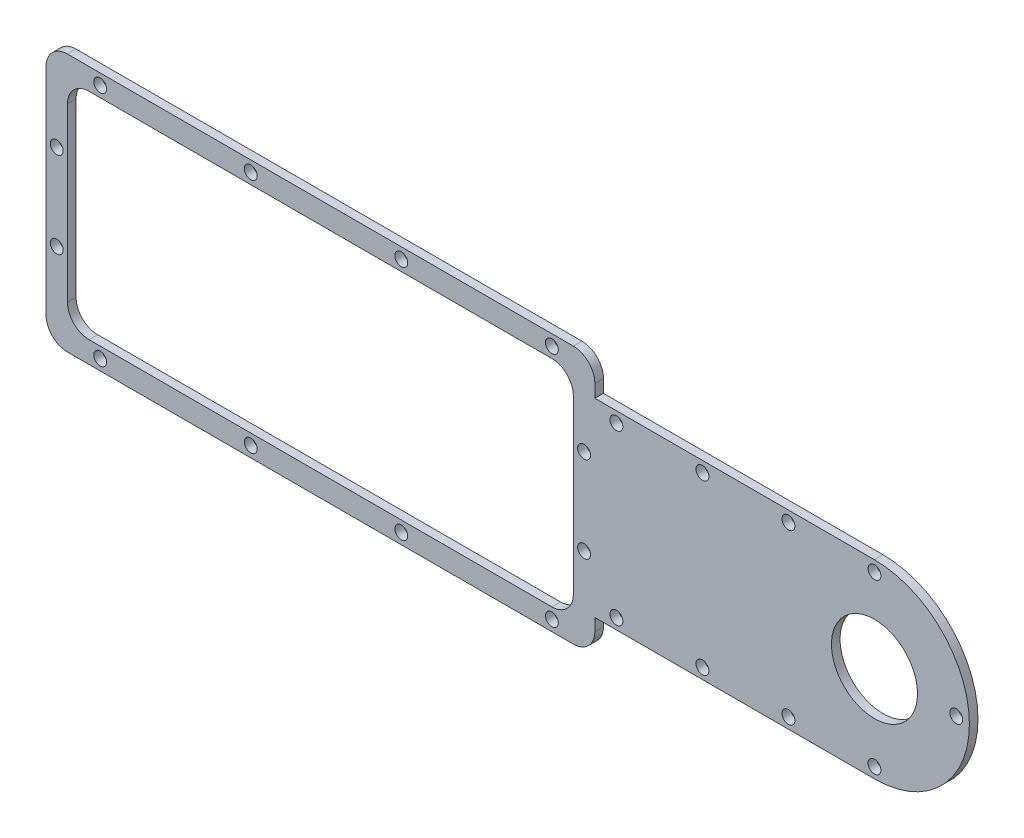
SolidWorks part; units mm, degrees
material "ABS"
ref_plane "Front Plane" through (0, 0, 0) normal (0, 0, 1) x (1, 0, 0)
ref_plane "Top Plane" through (0, 0, 0) normal (0, 1, 0) x (1, 0, 0)
ref_plane "Right Plane" through (0, 0, 0) normal (1, 0, 0) x (0, 0, -1)
sketch "Sketch1" plane through (0, 0, 0) normal (0, 0, 1) x (1, 0, 0)
  line L0 (63.8, 22) -> (128.81, 22)
  line L1 (-58.8, -30) -> (58.8, -30)
  line L2 (-63.8, -25) -> (-63.8, 25)
  line L3 (-58.8, 30) -> (58.8, 30)
  line L4 (63.8, -25) -> (63.8, 25)
  line L5 (-63.8, -30) -> (63.8, 30) construction
  line L6 (-63.8, 30) -> (63.8, -30) construction
  line L7 (63.8, -22.136) -> (128.81, -22.136)
  arc A0 (-63.8, -25) -> (-58.8, -30) centre (-58.8, -25) ccw
  arc A1 (58.8, -30) -> (63.8, -25) centre (58.8, -25) ccw
  arc A2 (63.8, 25) -> (58.8, 30) centre (58.8, 25) ccw
  arc A3 (-58.8, 30) -> (-63.8, 25) centre (-58.8, 25) ccw
  circle A4 centre (128.81, 0) radius 10
  arc A5 (128.81, 22) -> (128.81, -22.136) centre (128.81, -0.068) cw
  point P0 (0, 0)
  dimension "D2" = 5
  dimension "D5" = 20
  dimension "D7" = 22.136
  dimension "D4" = 22
  dimension "D1" = 60
  dimension "D3" = 117.6
  dimension "D6" = 192.61
extrude "Boss-Extrude1" add sketch "Sketch1" along normal blind 2 contours A5 L0 L4 L7 A4 | L3 A3 L2 A0 L1 A1 L4 A2
sketch "Sketch2" plane through (0, 0, 2) normal (0, 0, 1) x (1, 0, 0)
  line L7 (58.8, 17) -> (58.8, -17.136)
  line L8 (-63.8, -25) -> (-63.8, 25) construction
  line L9 (-58.8, 30) -> (58.8, 30) construction
  line L14 (128.81, 17) -> (58.8, 17)
  line L15 (58.8, 17) -> (58.8, 25)
  line L16 (58.8, 25) -> (-58.8, 25)
  line L17 (-58.8, 25) -> (-58.8, -25)
  line L18 (-58.8, -25) -> (58.8, -25)
  line L19 (58.8, -25) -> (58.8, -17.136)
  line L20 (58.8, -17.136) -> (128.81, -17.136)
  line L22 (58.8, 17) -> (58.8, 25)
  line L23 (58.8, 25) -> (-58.8, 25)
  line L24 (-58.8, 25) -> (-58.8, -25)
  line L25 (-58.8, -25) -> (58.8, -25)
  line L26 (58.8, -25) -> (58.8, -17.136)
  circle A5 centre (-53.8, 27.5) radius 1.5
  circle A6 centre (-61.3, 10) radius 1.5
  arc A10 (128.81, -17.136) -> (128.81, 17) centre (128.81, -0.068) ccw
  dimension "D3" = 3
  dimension "D6" = 3
  dimension "D2" = 34.136
  dimension "D4" = 10
  dimension "D5" = 2.5
  dimension "D7" = 2.5
  dimension "D8" = 20
  dimension "D1" = 5
extrude "Cut-Extrude1" cut sketch "Sketch2" against normal blind 5 contours L22 L23 L24 L25 L26 L7
fillet "Fillet1" radius 5 4 edges at (58.8, 25, 1) (58.8, -25, 1) (-58.8, -25, 1) (-58.8, 25, 1)
sketch "Sketch3" plane through (0, 0, 2) normal (0, 0, 1) x (1, 0, 0)
  line L0 (-58.8, 30) -> (58.8, 30) construction
  line L1 (-63.8, -25) -> (-63.8, 25) construction
  line L2 (-58.8, 20) -> (-58.8, -20) construction
  line L3 (0, 0) -> (0, 6.5983)
  circle A0 centre (-51.2, 27.5) radius 1.5
  circle A1 centre (-16.2, 27.5) radius 1.5
  circle A2 centre (18.8, 27.5) radius 1.5
  circle A3 centre (53.8, 27.5) radius 1.5
  circle A4 centre (-16.2, -27.5) radius 1.5
  circle A5 centre (18.8, -27.5) radius 1.5
  circle A6 centre (53.8, -27.5) radius 1.5
  circle A7 centre (-51.2, -27.5) radius 1.5
  circle A8 centre (-61.3, 10) radius 1.5
  circle A9 centre (-61.3, -10) radius 1.5
  circle A10 centre (61.3, -10) radius 1.5
  circle A11 centre (61.3, 10) radius 1.5
  dimension "D1" = 3
  dimension "D3" = 12.6
  dimension "D6" = 3
  dimension "D9" = 3
  dimension "D10" = 20
  dimension "D11" = 2.5
  dimension "D2" = 2.5
  dimension "D7" = 2.5
  dimension "D8" = 20
  dimension "D12" = 6.5983
  dimension "D4" = 4
  dimension "D5" = 2
extrude "Cut-Extrude2" cut sketch "Sketch3" against normal blind 5 contours A0 | A1 | A2 | A3 | A11 | A10 | A6 | A5 | A4 | A7 | A9 | A8
sketch "Sketch4" plane through (0, 0, 2) normal (0, 0, 1) x (1, 0, 0)
  line L0 (63.8, 22) -> (128.81, 22) construction
  circle A0 centre (68.81, 19.5) radius 1.5
  arc A1 (128.81, -22.136) -> (128.81, 22) centre (128.81, -0.068) ccw construction
  circle A2 centre (88.81, 19.5) radius 1.5
  circle A3 centre (108.81, 19.5) radius 1.5
  circle A4 centre (128.81, 19.5) radius 1.5
  circle A5 centre (88.81, -19.66) radius 1.5
  circle A6 centre (108.81, -19.66) radius 1.5
  circle A7 centre (128.81, -19.66) radius 1.5
  circle A8 centre (68.81, -19.66) radius 1.5
  circle A9 centre (147.81, 0) radius 1.5
  dimension "D1" = 3
  dimension "D2" = 2.5
  dimension "D3" = 60
  dimension "D6" = 3
  dimension "D8" = 22
  dimension "D7" = 19
  dimension "D4" = 4
  dimension "D5" = 2
extrude "Cut-Extrude3" cut sketch "Sketch4" against normal through all
